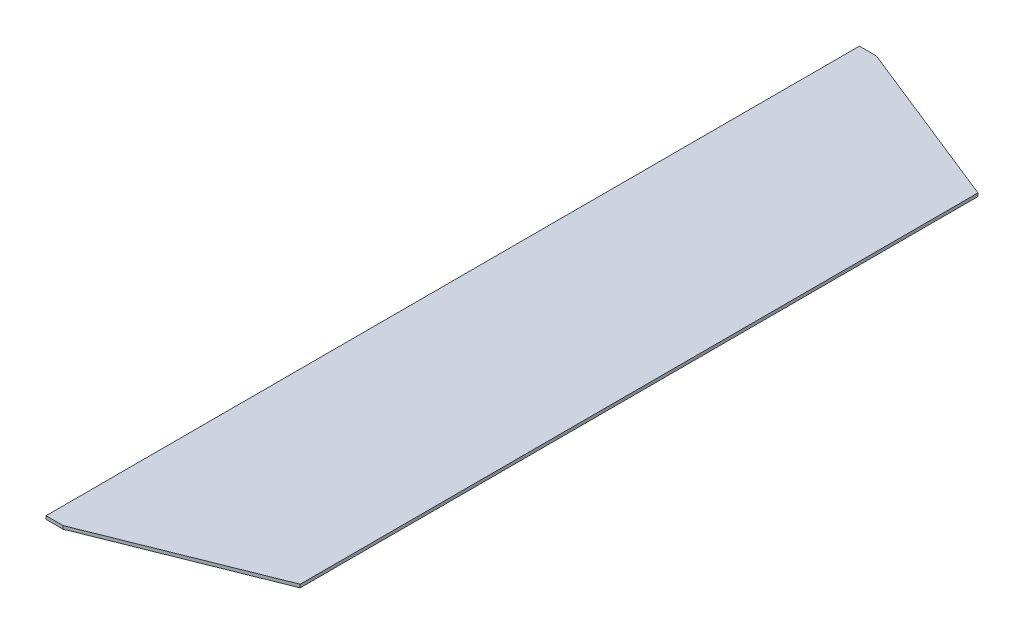
SolidWorks part; units mm, degrees
material "3003 Alloy"
ref_plane "Front Plane" through (0, 0, 0) normal (0, 0, 1) x (1, 0, 0)
ref_plane "Top Plane" through (0, 0, 0) normal (0, 1, 0) x (1, 0, 0)
ref_plane "Right Plane" through (0, 0, 0) normal (1, 0, 0) x (0, 0, -1)
sketch "Sketch1" plane through (0, 0, 0) normal (0, 0, 1) x (1, 0, 0)
  line L0 (0, 0.5969) -> (0, -0.5969)
  line L1 (-34.925, 0) -> (34.925, 0) construction
  point P0 (-34.925, 0.5969)
  point P6 (0, 0)
  point P7 (-34.925, -0.5969)
sketch "Sketch2" plane through (0, 0, 0) normal (1, 0, 0) x (0, 0, -1)
  line L0 (152.4, 0) -> (-152.4, 0)
  line L1 (152.4, -0.5969) -> (152.4, 0.5969) construction
  point P4 (0, 0)
  point P7 (152.4, 0)
  point P8 (152.4, -0.5969)
  point P9 (152.4, 0.5969)
  dimension "D1" = 1.1938
sketch "Sketch3" plane through (0, 0, 0) normal (0, 0, 1) x (1, 0, 0)
  line L1 (34.925, 0.5969) -> (-34.925, 0.5969)
  line L2 (34.925, 0.5969) -> (34.925, -0.5969)
  line L3 (34.925, -0.5969) -> (-34.925, -0.5969)
  line L4 (-34.925, 0.5969) -> (-34.925, -0.5969)
  line L5 (34.925, 0.5969) -> (-34.925, -0.5969) construction
  line L6 (34.925, -0.5969) -> (-34.925, 0.5969) construction
  point P0 (0, 0)
extrude "Boss-Extrude1" add sketch "Sketch3" along normal up to vertex (152.4 mm away) and the other way up to vertex (152.4 mm away) up to point (0, 0, 152.4) other way up to point (0, 0, -152.4)
sketch "Sketch4" plane through (0, 0, 0) normal (0, 1, 0) x (1, 0, 0)
  line L1 (34.925, -152.4) -> (-34.925, -152.4) construction
  line L2 (34.925, -152.4) -> (34.925, 152.4) construction
  line L3 (34.925, 152.4) -> (-34.925, 152.4) construction
  line L4 (-34.925, -152.4) -> (-34.925, 152.4) construction
  line L5 (34.925, -152.4) -> (-34.925, 152.4) construction
  line L6 (34.925, 152.4) -> (-34.925, -152.4) construction
  point P0 (0, 0)
  point P6 (-34.925, 152.4)
  point P10 (34.925, 152.4)
  point P11 (34.925, -152.4)
sketch "Sketch5" plane through (0, -0.5969, 0) normal (0, -1, 0) x (1, 0, 0)
  line L0 (-28.575, 152.4) -> (34.925, 127)
  line L1 (-34.925, 152.4) -> (34.925, 152.4) construction
  line L2 (34.925, 152.4) -> (34.925, -152.4) construction
  line L3 (34.925, 127) -> (34.925, -127)
  line L4 (34.925, -127) -> (-28.575, -152.4)
  line L5 (-34.925, -152.4) -> (34.925, -152.4) construction
  line L6 (-28.575, -152.4) -> (-34.925, -152.4)
  line L7 (-34.925, -152.4) -> (-34.925, 152.4)
  line L8 (-34.925, 152.4) -> (-28.575, 152.4)
  dimension "D1" = 63.5
  dimension "D2" = 25.4
  dimension "D4" = 25.4
extrude "Cut-Extrude2" cut sketch "Sketch5" against normal through all flip side to cut
equation "\"D1@Sketch2\"=\"Wire Dia@Sketch1\""
